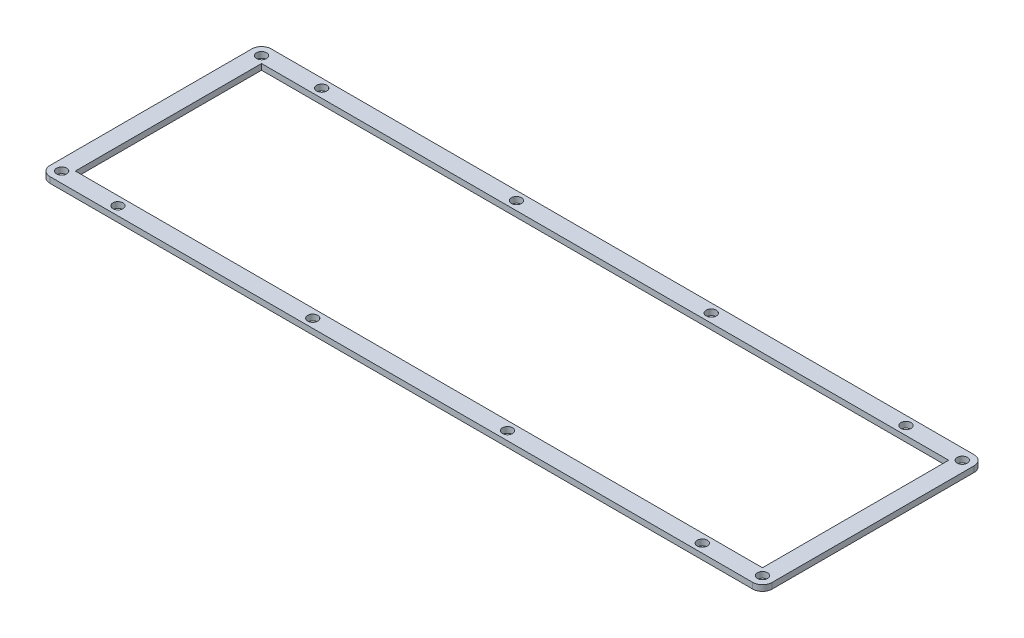
SolidWorks part; units mm, degrees
ref_plane "Front Plane" through (0, 0, 0) normal (0, 0, 1) x (1, 0, 0)
ref_plane "Top Plane" through (0, 0, 0) normal (0, 1, 0) x (1, 0, 0)
ref_plane "Right Plane" through (0, 0, 0) normal (1, 0, 0) x (0, 0, -1)
sketch "Sketch1" plane through (0, 0, 0) normal (0, 1, 0) x (1, 0, 0)
  line L0 (0, 108.6) -> (0, 5)
  line L1 (9, 104.6) -> (9, 9)
  line L2 (365.775, 0) -> (5, 0)
  line L3 (361.775, 9) -> (9, 9)
  line L4 (370.775, 108.6) -> (370.775, 5)
  line L5 (361.775, 104.6) -> (361.775, 9)
  line L6 (365.775, 113.6) -> (5, 113.6)
  line L7 (361.775, 104.6) -> (9, 104.6)
  arc A0 (365.775, 0) -> (370.775, 5) centre (365.775, 5) ccw
  arc A1 (370.775, 108.6) -> (365.775, 113.6) centre (365.775, 108.6) ccw
  arc A2 (0, 5) -> (5, 0) centre (5, 5) ccw
  circle A3 centre (5.5, 108.1) radius 2.6
  circle A4 centre (5.5, 5.5) radius 2.6
  circle A5 centre (365.275, 5.5) radius 2.6
  circle A6 centre (365.275, 108.1) radius 2.6
  arc A7 (5, 113.6) -> (0, 108.6) centre (5, 108.6) ccw
  circle A8 centre (35.3875, 4.5) radius 2.6
  circle A9 centre (135.3875, 4.5) radius 2.6
  circle A10 centre (335.3875, 4.5) radius 2.6
  circle A11 centre (235.3875, 4.5) radius 2.6
  circle A12 centre (35.3875, 109.1) radius 2.6
  circle A13 centre (135.3875, 109.1) radius 2.6
  circle A14 centre (335.3875, 109.1) radius 2.6
  circle A15 centre (235.3875, 109.1) radius 2.6
extrude "Boss-Extrude1" add sketch "Sketch1" against normal blind 3
